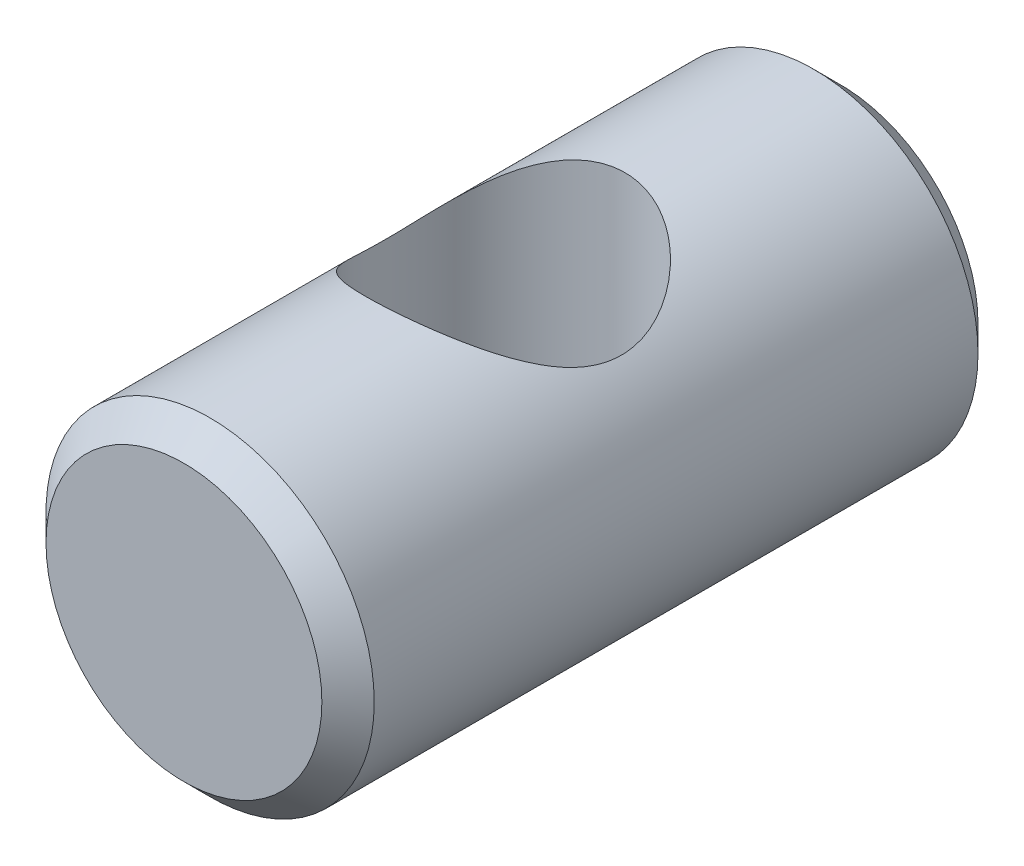
SolidWorks part; units mm, degrees
ref_plane "Front Plane" through (0, 0, 0) normal (0, 0, 1) x (1, 0, 0)
ref_plane "Top Plane" through (0, 0, 0) normal (0, 1, 0) x (1, 0, 0)
ref_plane "Right Plane" through (0, 0, 0) normal (1, 0, 0) x (0, 0, -1)
sketch "Sketch2" plane through (0, 0, 0) normal (0, 0, 1) x (1, 0, 0)
  circle A0 centre (0, 0) radius 4.765
  dimension "D1" = 9.53
extrude "Boss-Extrude1" add sketch "Sketch2" along normal mid plane 19.05
sketch "Sketch3" plane through (0, 0, 0) normal (0, 1, 0) x (1, 0, 0)
  circle A0 centre (-0.25, 0) radius 3.43
  dimension "D1" = 6.86
  dimension "D2" = 0.25
extrude "Cut-Extrude1" cut sketch "Sketch3" against normal through all both and the other way through all
chamfer "Chamfer1" distance 0.76 2 edges at (4.765, 0, -9.525) (4.765, 0, 9.525)
